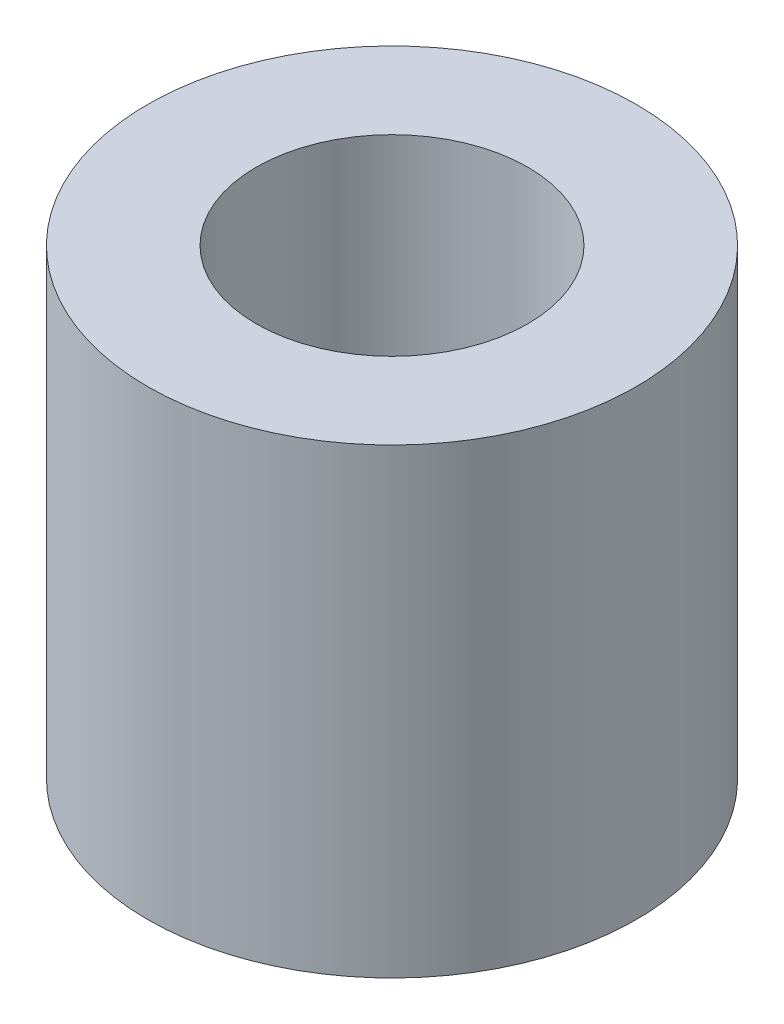
SolidWorks part; units mm, degrees
material "Brass"
ref_plane "Front Plane" through (0, 0, 0) normal (0, 0, 1) x (1, 0, 0)
ref_plane "Top Plane" through (0, 0, 0) normal (0, 1, 0) x (1, 0, 0)
ref_plane "Right Plane" through (0, 0, 0) normal (1, 0, 0) x (0, 0, -1)
sketch "Sketch1" plane through (0, 0, 0) normal (0, 1, 0) x (1, 0, 0)
  circle A0 centre (0, 0) radius 1.8
  circle A1 centre (0, 0) radius 1
  dimension "D1" = 3.6
  dimension "D2" = 2
extrude "Boss-Extrude1" add sketch "Sketch1" along normal blind 3.4
